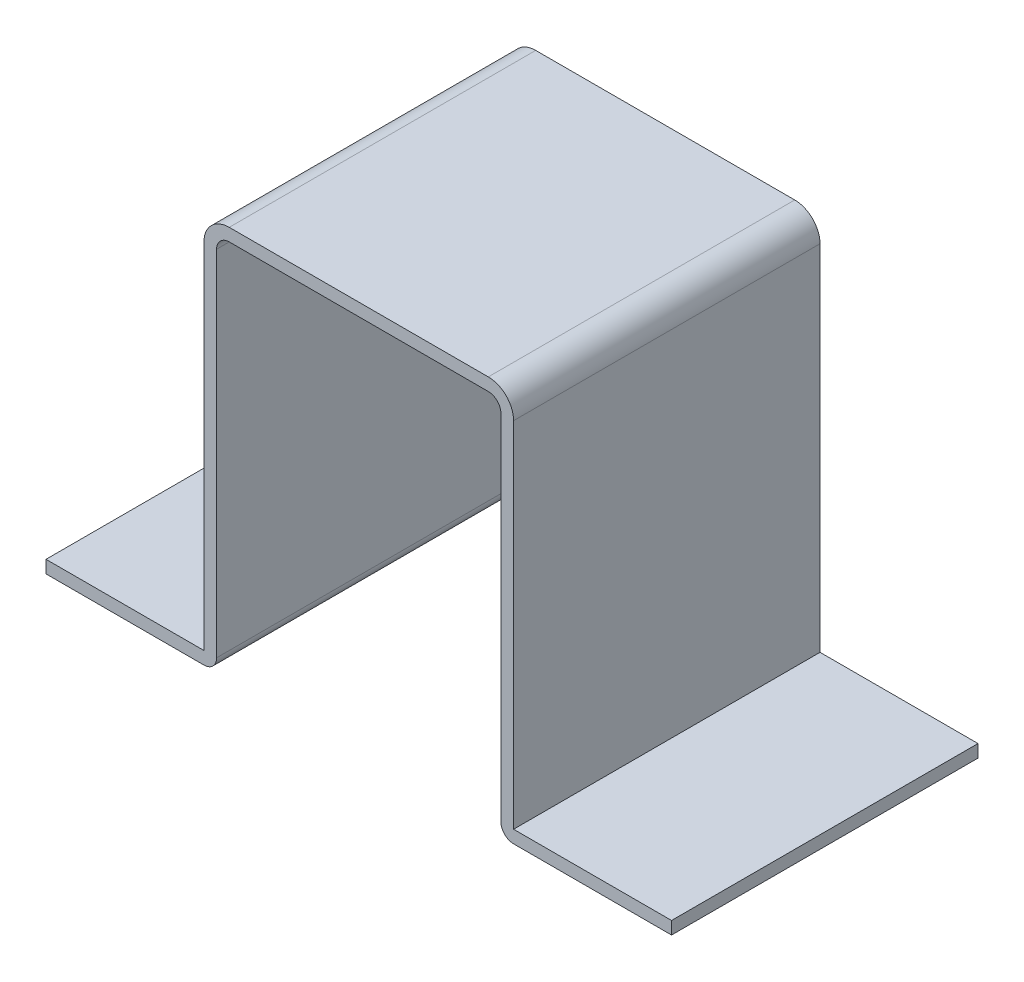
SolidWorks part; units mm, degrees
ref_plane "Alzado" through (0, 0, 0) normal (0, 0, 1) x (1, 0, 0)
ref_plane "Planta" through (0, 0, 0) normal (0, 1, 0) x (1, 0, 0)
ref_plane "Vista lateral" through (0, 0, 0) normal (1, 0, 0) x (0, 0, -1)
sketch "Croquis1" plane through (0, 0, 0) normal (0, 0, 1) x (1, 0, 0)
  line L0 (24.5, -30) -> (49.5, -30)
  line L1 (-24.5, -30) -> (-49.5, -30)
  line L2 (22.5, -28) -> (22.5, 28)
  line L3 (20.5, 30) -> (-20.5, 30)
  line L4 (-22.5, -28) -> (-22.5, 28)
  line L5 (22.5, -30) -> (-22.5, 30) construction
  line L6 (22.5, 30) -> (-22.5, -30) construction
  line L7 (24.5, -28) -> (49.5, -28)
  line L8 (24.5, -28) -> (24.5, 28)
  line L9 (20.5, 32) -> (-20.5, 32)
  line L10 (-24.5, -28) -> (-24.5, 28)
  line L11 (-24.5, -28) -> (-49.5, -28)
  line L12 (-49.5, -28) -> (-49.5, -30)
  line L13 (49.5, -28) -> (49.5, -30)
  arc A0 (24.5, -30) -> (22.5, -28) centre (24.5, -28) cw
  arc A1 (22.5, 28) -> (20.5, 30) centre (20.5, 28) ccw
  arc A2 (-20.5, 30) -> (-22.5, 28) centre (-20.5, 28) ccw
  arc A3 (-24.5, -30) -> (-22.5, -28) centre (-24.5, -28) ccw
  arc A4 (24.5, -28) -> (24.5, -28) centre (24.5, -28) cw
  arc A5 (24.5, 28) -> (20.5, 32) centre (20.5, 28) ccw
  arc A6 (-20.5, 32) -> (-24.5, 28) centre (-20.5, 28) ccw
  arc A7 (-24.5, -28) -> (-24.5, -28) centre (-24.5, -28) ccw
  point P0 (0, 0)
  dimension "D5" = 2
  dimension "D1" = 45
  dimension "D2" = 60
  dimension "D3" = 27
  dimension "D4" = 27
  dimension "D6" = 2
extrude "Saliente-Extruir1" add sketch "Croquis1" along normal mid plane 48.5
